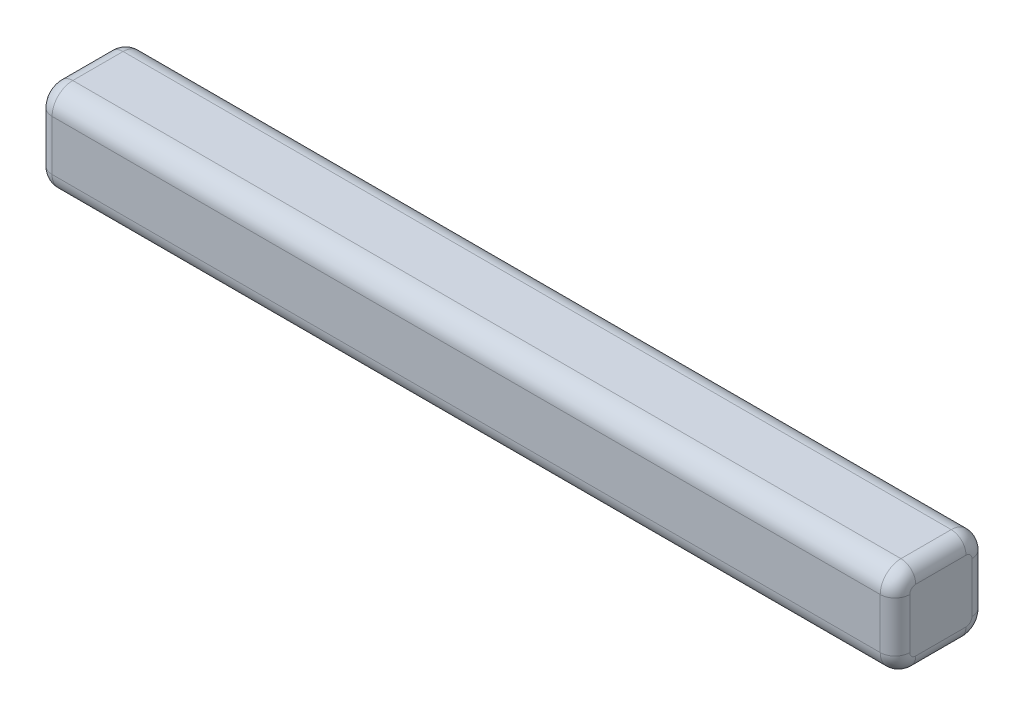
SolidWorks part; units mm, degrees
ref_plane "Front Plane" through (0, 0, 0) normal (0, 0, 1) x (1, 0, 0)
ref_plane "Top Plane" through (0, 0, 0) normal (0, 1, 0) x (1, 0, 0)
ref_plane "Right Plane" through (0, 0, 0) normal (1, 0, 0) x (0, 0, -1)
sketch "Sketch2" plane through (0, 0, 0) normal (1, 0, 0) x (0, 0, -1)
  line L0 (-37.1936, 144.174) -> (-40.3936, 144.174) construction
  line L5 (-40.3436, 141.024) -> (-37.2436, 141.024)
  line L6 (-40.3436, 141.024) -> (-40.3436, 144.124)
  line L7 (-40.3436, 144.124) -> (-37.2436, 144.124)
  line L8 (-37.2436, 141.024) -> (-37.2436, 144.124)
  line L9 (-37.1936, 140.974) -> (-40.3936, 140.974) construction
  line L10 (-37.1936, 144.174) -> (-37.1936, 140.974) construction
  line L11 (-40.3936, 144.174) -> (-40.3936, 140.974) construction
  dimension "D1" = 0.05
  dimension "D2" = 0.05
  dimension "D3" = 0.05
  dimension "D4" = 0.05
extrude "Boss-Extrude1" add sketch "Sketch2" along normal up to surface (29 mm away) from surface at 11.4401
fillet "Fillet1" radius 0.7 4 edges at (25.9401, 144.124, 37.2436) (25.9401, 144.124, 40.3436) (25.9401, 141.024, 37.2436) (25.9401, 141.024, 40.3436)
fillet "Fillet3" radius 0.5 16 edges at (40.4401, 141.2291, 37.4486) (40.4401, 141.024, 38.7936) (40.4401, 141.2291, 40.1385) (40.4401, 142.574, 40.3436) (40.4401, 143.919, 40.1385) (40.4401, 144.124, 38.7936) (40.4401, 143.919, 37.4486) (40.4401, 142.574, 37.2436) (11.4401, 143.919, 40.1385) (11.4401, 142.574, 40.3436) (11.4401, 141.2291, 40.1385) (11.4401, 141.024, 38.7936) (11.4401, 141.2291, 37.4486) (11.4401, 142.574, 37.2436) (11.4401, 143.919, 37.4486) (11.4401, 144.124, 38.7936)
